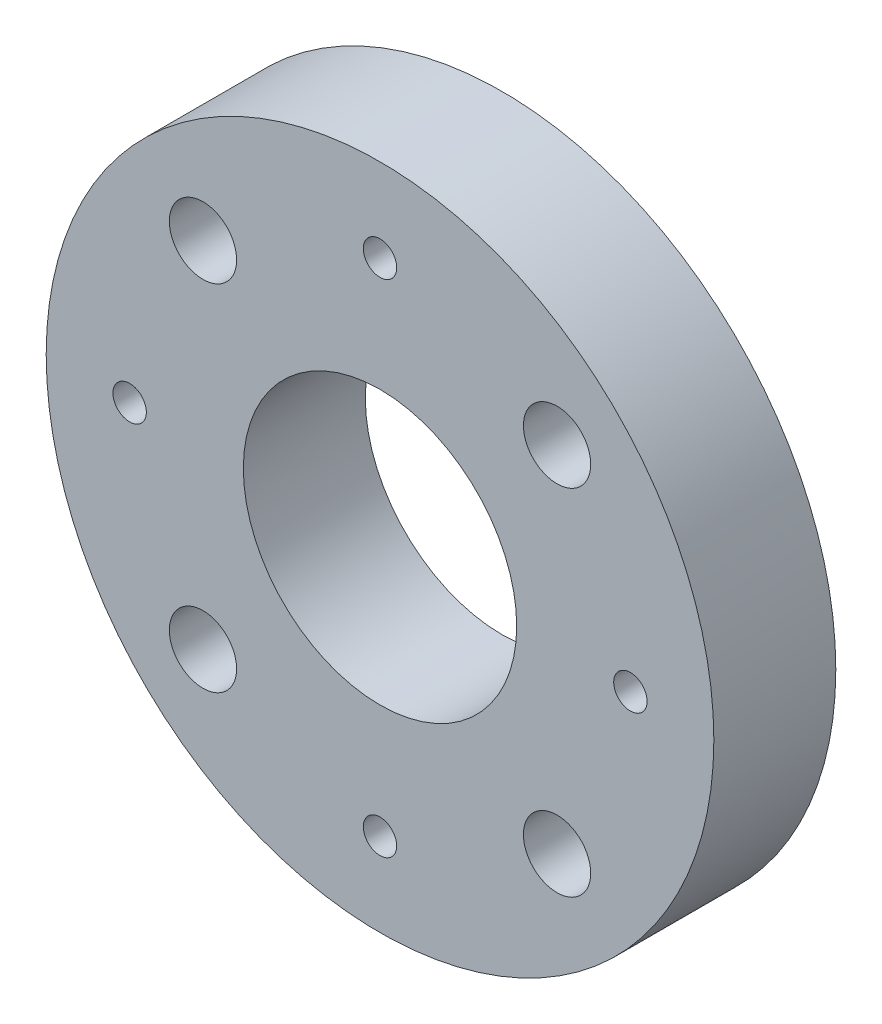
SolidWorks part; units mm, degrees
material "Acrylic (Medium-high impact)"
ref_plane "Front Plane" through (0, 0, 0) normal (0, 0, 1) x (1, 0, 0)
ref_plane "Top Plane" through (0, 0, 0) normal (0, 1, 0) x (1, 0, 0)
ref_plane "Right Plane" through (0, 0, 0) normal (1, 0, 0) x (0, 0, -1)
sketch "Sketch1" plane through (0, 0, 0) normal (0, 0, 1) x (1, 0, 0)
  line L0 (0, 0) -> (0, 11.9062) construction
  line L1 (-11.9062, 0) -> (0, 0) construction
  line L2 (0, 0) -> (0, -11.9062) construction
  line L3 (0, 0) -> (11.9062, 0) construction
  circle A0 centre (0, 0) radius 15.875
  circle A1 centre (0, 0) radius 6.5
  circle A2 centre (0, 11.9062) radius 0.7937
  circle A3 centre (-11.9062, 0) radius 0.7937
  circle A4 centre (0, -11.9062) radius 0.7937
  circle A5 centre (11.9062, 0) radius 0.7937
  dimension "D1" = 13
  dimension "D2" = 31.75
  dimension "D3" = 1.5875
  dimension "D4" = 11.9062
extrude "Boss-Extrude1" add sketch "Sketch1" along normal blind 5.8
hole_wizard "M3 Clearance Hole1" positions "Sketch3" profile "Sketch2" hole size "M3" standard "Ansi Metric"
sketch "Sketch3" plane through (0, 0, 5.8) normal (0, 0, 1) x (1, 0, 0)
  line L0 (-8.419, 8.419) -> (8.419, 8.419) construction
  line L1 (8.419, 8.419) -> (8.419, -8.419) construction
  line L2 (8.419, -8.419) -> (-8.419, -8.419) construction
  line L3 (-8.419, -8.419) -> (-8.419, 8.419) construction
  circle A0 centre (0, 0) radius 11.9062 construction
  point P0 (-8.419, 8.419)
  point P1 (8.419, 8.419)
  point P3 (8.419, -8.419)
  point P5 (-8.419, -8.419)
sketch "Sketch2" plane through (-8.419, 8.419, 5.8) normal (1, 0, 0) x (0, -1, 0)
  line L0 (0, 0) -> (0, 6.7614)
  line L1 (0, 6.7614) -> (1.6, 5.8)
  line L2 (1.6, 5.8) -> (1.6, 0)
  line L5 (1.6, 0) -> (0, 0)
  line L10 (0, 6.7614) -> (-1.6, 5.8) construction
  line L11 (0, -6.35) -> (0, 107.95) construction
  dimension "Hole Dia." = 3.2
  dimension "Hole Depth" = 5.8
  dimension "Drill Angle" = 118
